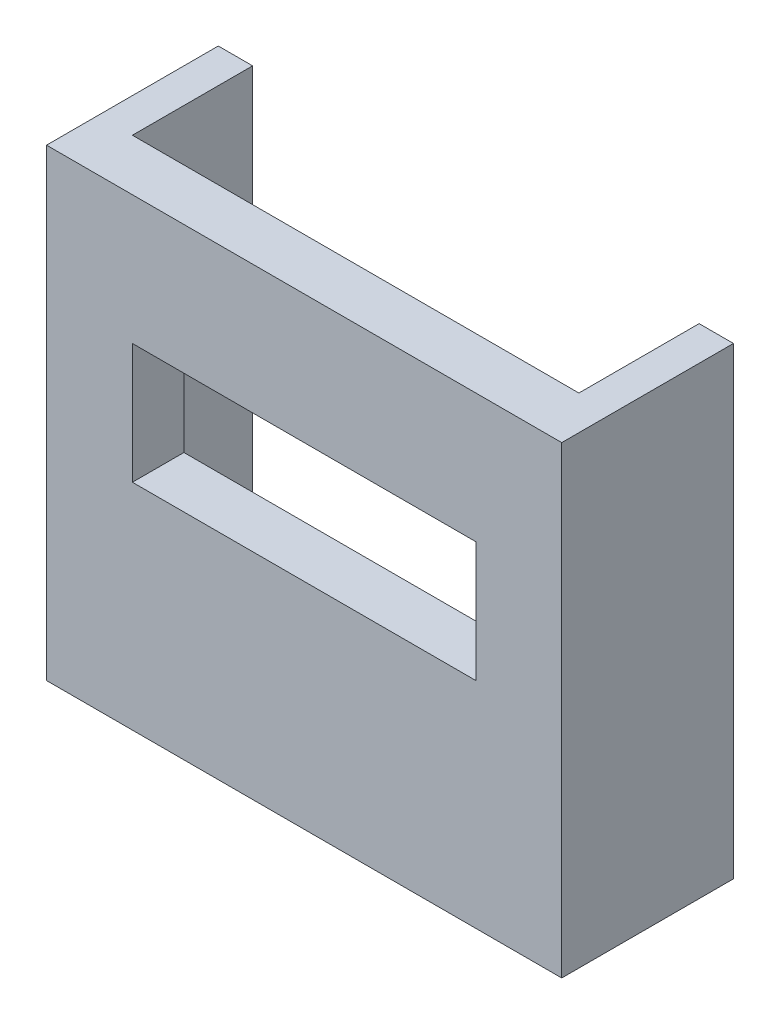
SolidWorks part; units mm, degrees
ref_plane "Alzado" through (0, 0, 0) normal (0, 0, 1) x (1, 0, 0)
ref_plane "Planta" through (0, 0, 0) normal (0, 1, 0) x (1, 0, 0)
ref_plane "Vista lateral" through (0, 0, 0) normal (1, 0, 0) x (0, 0, -1)
sketch "Croquis1" plane through (0, 0, 0) normal (0, 1, 0) x (1, 0, 0)
  line L1 (0, 0) -> (-30, 0)
  line L2 (0, 0) -> (0, -10)
  line L3 (0, -10) -> (-30, -10)
  line L4 (-30, 0) -> (-30, -10)
  dimension "D1" = 30
  dimension "D2" = 10
extrude "Saliente-Extruir1" add sketch "Croquis1" along normal blind 30
sketch "Croquis2" plane through (0, 0, 10) normal (0, 0, 1) x (1, 0, 0)
  line L0 (-15, 0) -> (-15, 12.5) construction
  line L1 (-30, 0) -> (0, 0) construction
  line L2 (-25, 16) -> (-30, 16) construction
  line L3 (-25, 12.5) -> (-5, 12.5)
  line L4 (-25, 12.5) -> (-25, 19.5)
  line L7 (-30, 30) -> (-30, 0) construction
  line L8 (-25, 19.5) -> (-5, 19.5)
  line L9 (-5, 12.5) -> (-5, 19.5)
  point P13 (-15, 19.5)
  dimension "D1" = 10
  dimension "D2" = 7
  dimension "D3" = 12.5
extrude "Cortar-Extruir1" cut sketch "Croquis2" against normal up to next
sketch "Croquis4" plane through (0, 0, 0) normal (0, 0, -1) x (-1, 0, 0)
  line L0 (30, 30) -> (30, 0) construction
  line L1 (2, 27) -> (28, 27)
  line L2 (2, 27) -> (2, 3)
  line L3 (2, 3) -> (28, 3)
  line L4 (28, 27) -> (28, 3)
  line L5 (0, 30) -> (0, 0) construction
  line L7 (0, 30) -> (30, 30) construction
  line L8 (0, 0) -> (30, 0) construction
  dimension "D1" = 2
  dimension "D2" = 2
  dimension "D3" = 3
  dimension "D4" = 3
extrude "Cortar-Extruir3" cut sketch "Croquis4" against normal blind 7
sketch "Croquis5" plane through (0, 3, 0) normal (0, 1, 0) x (1, 0, 0)
  line L0 (-2, 0) -> (-28, 0) construction
  circle A0 centre (-15, 0) radius 2.5
  dimension "D1" = 5
extrude "Cortar-Extruir4" cut sketch "Croquis5" against normal up to next
sketch "Croquis6" plane through (0, 30, 0) normal (0, 1, 0) x (1, 0, 0)
  line L12 (0, -10) -> (0, 0)
  line L13 (0, 0) -> (-30, 0)
  line L14 (-30, 0) -> (-30, -10)
  line L15 (-30, -10) -> (0, -10)
  line L16 (0, -10) -> (0, 0)
  line L17 (0, 0) -> (-30, 0)
  line L18 (-30, 0) -> (-30, -10)
  line L19 (-30, -10) -> (0, -10)
  dimension "D1" = 0
extrude "Cortar-Extruir5" cut sketch "Croquis6" against normal up to surface (3 mm away) up to face at (-15, 27, 3.5)
